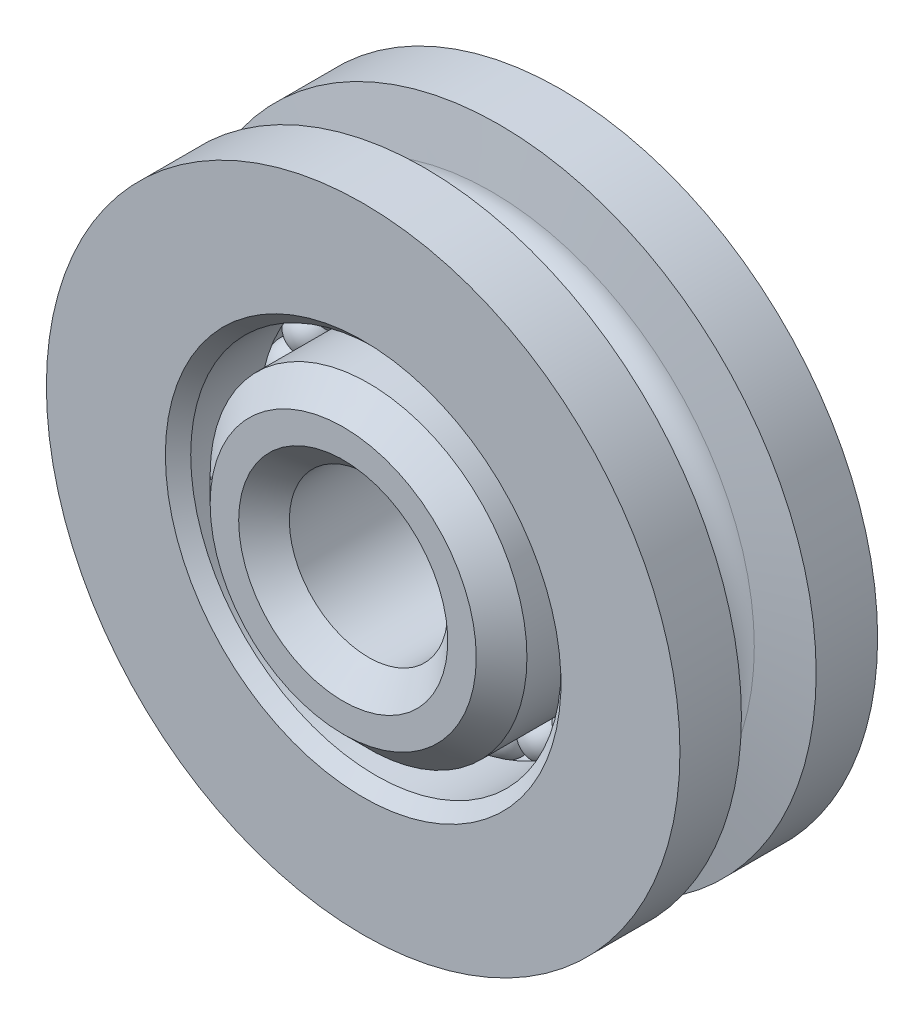
SolidWorks part; units mm, degrees
material "Alloy Steel"
ref_plane "Front" through (0, 0, 0) normal (0, 0, 1) x (1, 0, 0)
ref_plane "Top" through (0, 0, 0) normal (0, 1, 0) x (1, 0, 0)
ref_plane "Right" through (0, 0, 0) normal (1, 0, 0) x (0, 0, -1)
sketch "Sketch1" plane through (0, 0, 0) normal (1, 0, 0) x (0, 0, -1)
  line L0 (0.7493, 6.35) -> (1.9812, 6.35)
  line L1 (-0.7493, 6.35) -> (-1.9812, 6.35)
  line L2 (-0.7493, 6.35) -> (-0.5888, 5.2703)
  line L3 (0.3572, 3.7108) -> (1.9812, 3.7108)
  line L4 (2.3812, 1.5875) -> (-2.3812, 1.5875)
  line L5 (-0.3572, 3.175) -> (-2.3813, 3.175)
  line L6 (0.7493, 6.35) -> (0.5888, 5.2703)
  line L8 (-2.3812, 0) -> (2.3812, 0) construction
  line L10 (1.9812, 6.35) -> (1.9812, 3.7108)
  line L13 (-2.3813, 3.175) -> (-2.3812, 1.5875)
  line L14 (0, 4.7625) -> (0, -4.7625) construction
  line L16 (2.3813, 3.175) -> (2.3812, 1.5875)
  line L17 (-1.9812, 6.35) -> (-1.9812, -6.35) construction
  line L18 (-1.9812, 3.7108) -> (-0.3572, 3.7108)
  line L20 (2.3813, 3.175) -> (0.3572, 3.175)
  line L21 (-1.9812, 3.7108) -> (-1.9812, 6.35)
  arc A0 (-0.5888, 5.2703) -> (0.5888, 5.2703) centre (0, 5.3578) ccw
  circle A1 centre (0, 5.3578) radius 0.5953 construction
  circle A2 centre (0, 0) radius 1.5875 construction
  circle A3 centre (0, 0) radius 3.175 construction
  arc A4 (-0.3572, 3.175) -> (0.3572, 3.175) centre (0, 3.4429) ccw
  circle A5 centre (0, -5.3578) radius 0.5953 construction
  arc A6 (0.3572, 3.7108) -> (-0.3572, 3.7108) centre (0, 3.4429) ccw
  point P28 (-1.9812, 0)
  dimension "Rope Dia" = 1.1906
  dimension "Shaft Dia" = 3.175
  dimension "D1" = 6.35
  dimension "D2" = 0.893
  dimension "Wd" = 4.7625
  dimension "D8" = 1.2319
  dimension "Groove Dia" = 9.525
  dimension "OD" = 12.7
  dimension "w Wd" = 3.9624
  dimension "D3" = 0.5358
  dimension "D4" = 5.3578
revolve "Revolve1" add sketch "Sketch1" angle 360 about L8
sketch "Sketch2" plane through (0, 0, 0) normal (1, 0, 0) x (0, 0, -1)
  line L0 (0, 4.7625) -> (0, -4.7625) construction
  line L1 (0, 3.8894) -> (0, 2.9964)
  arc A0 (0.3572, 3.7108) -> (-0.3572, 3.7108) centre (0, 3.4429) ccw construction
  arc A1 (0, 2.9964) -> (0, 3.8894) centre (0, 3.4429) ccw
revolve "Revolve2" add sketch "Sketch2" angle 360 about L1
pattern_circular "CirPattern1" count 24 over 360 about axis through (0, 0, 0) along (0, 0, 1) of bodies 117
chamfer "Chamfer1" distance 0.508 angle 45 4 edges at (1.5875, 0, -2.3812) (3.175, 0, -2.3813) (3.175, 0, 2.3813) (1.5875, 0, 2.3812)
chamfer "Chamfer2" distance 0.254 angle 45 2 edges at (3.7108, 0, -1.9812) (3.7108, 0, 1.9812)
ref_plane "Plane1" through (0, 0, 0) normal (0, 0, -1) x (-1, 0, 0)
equation "\"D1@Sketch1\"=\"Shaft Dia@Sketch1\" * 2"
equation "\"D2@Sketch1\" = \"Rope Dia@Sketch1\" * .75"
equation "\"D3@Sketch1\" = \"D2@Sketch1\" * .6"
